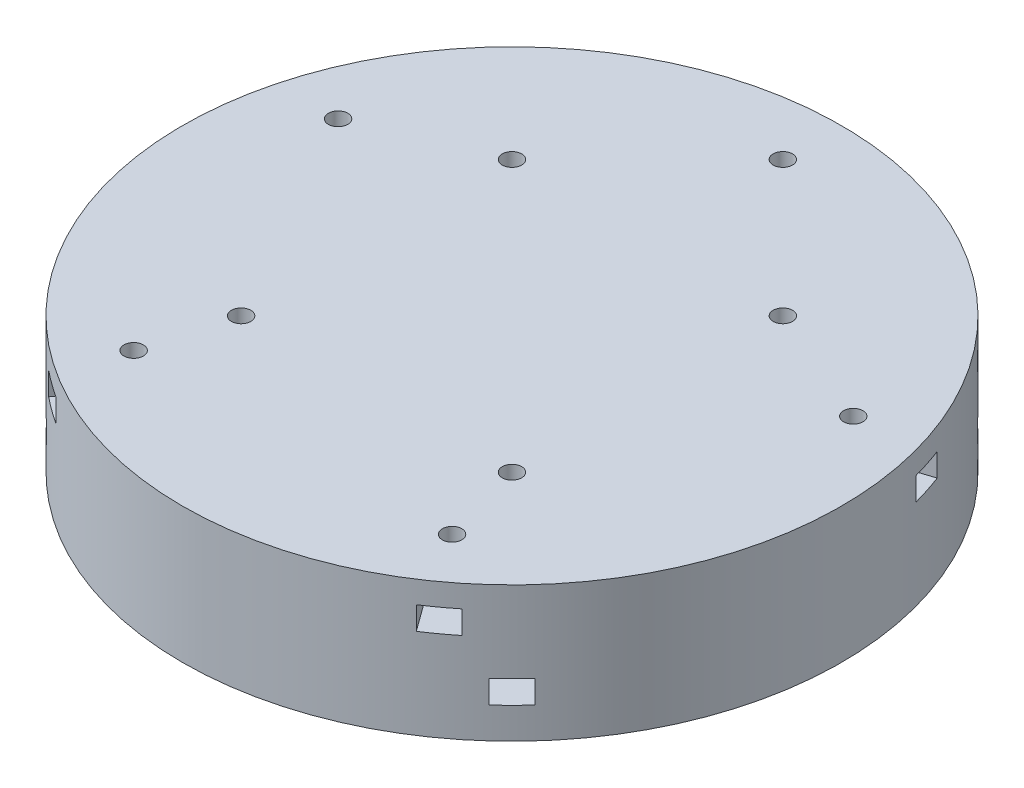
SolidWorks part; units mm, degrees
ref_plane "Front Plane" through (0, 0, 0) normal (0, 0, 1) x (1, 0, 0)
ref_plane "Top Plane" through (0, 0, 0) normal (0, 1, 0) x (1, 0, 0)
ref_plane "Right Plane" through (0, 0, 0) normal (1, 0, 0) x (0, 0, -1)
sketch "Sketch1" plane through (0, 0, 0) normal (0, 1, 0) x (1, 0, 0)
  line L0 (0, 30) -> (0, -30) construction
  line L1 (-30, -30) -> (30, -30) construction
  line L2 (-30, -30) -> (-30, 30) construction
  line L3 (-30, 30) -> (30, 30) construction
  line L4 (30, -30) -> (30, 30) construction
  line L5 (-30, -30) -> (30, 30) construction
  line L6 (-30, 30) -> (30, -30) construction
  line L7 (-30, 0) -> (30, 0) construction
  circle A0 centre (0, 0) radius 73
  circle A1 centre (30, 30) radius 2.15
  circle A3 centre (-30, 30) radius 2.15
  circle A4 centre (30, -30) radius 2.15
  circle A5 centre (-30, -30) radius 2.15
  circle A6 centre (0, 60) radius 2.15
  circle A7 centre (57.0634, 18.541) radius 2.15
  circle A8 centre (35.2671, -48.541) radius 2.15
  circle A9 centre (-35.2671, -48.541) radius 2.15
  circle A10 centre (-57.0634, 18.541) radius 2.15
  point P27 (0, 0)
  dimension "D1" = 146
  dimension "D4" = 4.3
  dimension "D5" = 60
  dimension "4.3" = 4.3
  dimension "D2" = 60
  dimension "D3" = 60
  dimension "D6" = 5
extrude "Boss-Extrude1" add sketch "Sketch1" along normal blind 30
ref_plane "Plane1" through (0, 12, 0) normal (0, 1, 0) x (1, 0, 0)
sketch "Sketch2" plane through (0, 12, 0) normal (0, 1, 0) x (1, 0, 0)
  line L0 (-30, 30) -> (0, 0) construction
  line L1 (-27.0402, 27.0402) -> (-25.9568, 31.0834)
  line L2 (-25.9568, 31.0834) -> (-28.9166, 34.0432)
  line L5 (-34.0432, 28.9166) -> (-31.0834, 25.9568)
  line L6 (-31.0834, 25.9568) -> (-27.0402, 27.0402)
  line L7 (-34.0432, 28.9166) -> (-54.1184, 48.9919)
  line L8 (-28.9166, 34.0432) -> (-48.9919, 54.1184)
  line L9 (28.9166, 34.0432) -> (25.9568, 31.0834)
  line L10 (-28.9166, 34.0432) -> (-30.9382, 33.5015) [skipped]
  line L11 (-33.5015, 30.9382) -> (-34.0432, 28.9166) [skipped]
  line L12 (25.9568, 31.0834) -> (27.0402, 27.0402)
  line L13 (27.0402, 27.0402) -> (31.0834, 25.9568)
  line L14 (31.0834, 25.9568) -> (34.0432, 28.9166)
  line L15 (34.0432, 28.9166) -> (54.1184, 48.9919)
  line L16 (28.9166, 34.0432) -> (48.9919, 54.1184)
  line L17 (34.0432, -28.9166) -> (31.0834, -25.9568)
  line L18 (31.0834, -25.9568) -> (27.0402, -27.0402)
  line L19 (27.0402, -27.0402) -> (25.9568, -31.0834)
  line L20 (25.9568, -31.0834) -> (28.9166, -34.0432)
  line L21 (28.9166, -34.0432) -> (48.9919, -54.1184)
  line L22 (34.0432, -28.9166) -> (54.1184, -48.9919)
  line L23 (-28.9166, -34.0432) -> (-25.9568, -31.0834)
  line L24 (-25.9568, -31.0834) -> (-27.0402, -27.0402)
  line L25 (-27.0402, -27.0402) -> (-31.0834, -25.9568)
  line L26 (-31.0834, -25.9568) -> (-34.0432, -28.9166)
  line L27 (-34.0432, -28.9166) -> (-54.1184, -48.9919)
  line L28 (-28.9166, -34.0432) -> (-48.9919, -54.1184)
  arc A0 (-32.5633, 27.4367) -> (-27.4367, 32.5633) centre (-30, 30) ccw construction
  circle A1 centre (0, 0) radius 73 construction
  arc A2 (-48.9919, 54.1184) -> (-54.1184, 48.9919) centre (0, 0) ccw
  arc A3 (54.1184, 48.9919) -> (48.9919, 54.1184) centre (0, 0) ccw
  arc A4 (48.9919, -54.1184) -> (54.1184, -48.9919) centre (0, 0) ccw
  arc A5 (-54.1184, -48.9919) -> (-48.9919, -54.1184) centre (0, 0) ccw
  point P42 (0, 0)
  dimension "D1" = 0
  dimension "D2" = 7.25
  dimension "D3" = 0
  dimension "D4" = 4
extrude "Cut-Extrude1" cut sketch "Sketch2" against normal blind 5.1
ref_plane "Plane2" through (0, 20, 0) normal (0, 1, 0) x (1, 0, 0)
sketch "Sketch4" plane through (0, 20, 0) normal (0, 1, 0) x (1, 0, 0)
  line L0 (-3.625, 62.0929) -> (-3.625, 72.9099)
  line L1 (0, 55.8142) -> (3.625, 57.9071)
  line L2 (3.625, 57.9071) -> (3.625, 62.0929)
  line L5 (-3.625, 62.0929) -> (-3.625, 57.9071)
  line L6 (-3.625, 57.9071) -> (0, 55.8142)
  line L7 (3.625, 62.0929) -> (3.625, 72.9099)
  line L8 (56.1931, 14.4467) -> (60.174, 15.7402)
  line L9 (-1.8125, 63.1393) -> (-3.625, 62.0929) [skipped]
  line L10 (3.625, 62.0929) -> (1.8125, 63.1393) [skipped]
  line L11 (53.0825, 17.2475) -> (56.1931, 14.4467)
  line L12 (53.9527, 21.3419) -> (53.0825, 17.2475)
  line L13 (57.9337, 22.6353) -> (53.9527, 21.3419)
  line L14 (57.9337, 22.6353) -> (68.2213, 25.978)
  line L15 (60.174, 15.7402) -> (70.4617, 19.0828)
  line L16 (31.1043, -48.9786) -> (33.5646, -52.3649)
  line L17 (32.8068, -45.1546) -> (31.1043, -48.9786)
  line L18 (36.9696, -44.7171) -> (32.8068, -45.1546)
  line L19 (39.43, -48.1035) -> (36.9696, -44.7171)
  line L20 (39.43, -48.1035) -> (45.7881, -56.8547)
  line L21 (33.5646, -52.3649) -> (39.9227, -61.1161)
  line L22 (-36.9696, -44.7171) -> (-39.43, -48.1035)
  line L23 (-32.8068, -45.1546) -> (-36.9696, -44.7171)
  line L24 (-31.1043, -48.9786) -> (-32.8068, -45.1546)
  line L25 (-33.5646, -52.3649) -> (-31.1043, -48.9786)
  line L26 (-33.5646, -52.3649) -> (-39.9227, -61.1161)
  line L27 (-39.43, -48.1035) -> (-45.7881, -56.8547)
  line L28 (-53.9527, 21.3419) -> (-57.9337, 22.6353)
  line L29 (-53.0825, 17.2475) -> (-53.9527, 21.3419)
  line L30 (-56.1931, 14.4467) -> (-53.0825, 17.2475)
  line L31 (-60.174, 15.7402) -> (-56.1931, 14.4467)
  line L32 (-60.174, 15.7402) -> (-70.4617, 19.0828)
  line L33 (-57.9337, 22.6353) -> (-68.2213, 25.978)
  circle A0 centre (0, 60) radius 3.625 construction
  circle A1 centre (0, 0) radius 73 construction
  arc A2 (3.625, 72.9099) -> (-3.625, 72.9099) centre (0, 0) ccw
  arc A3 (70.4617, 19.0828) -> (68.2213, 25.978) centre (0, 0) ccw
  arc A4 (39.9227, -61.1161) -> (45.7881, -56.8547) centre (0, 0) ccw
  arc A5 (-45.7881, -56.8547) -> (-39.9227, -61.1161) centre (0, 0) ccw
  arc A6 (-68.2213, 25.978) -> (-70.4617, 19.0828) centre (0, 0) ccw
  point P46 (0, 0)
  dimension "D1" = 7.25
  dimension "D2" = 5
extrude "Cut-Extrude2" cut sketch "Sketch4" along normal blind 5.1
